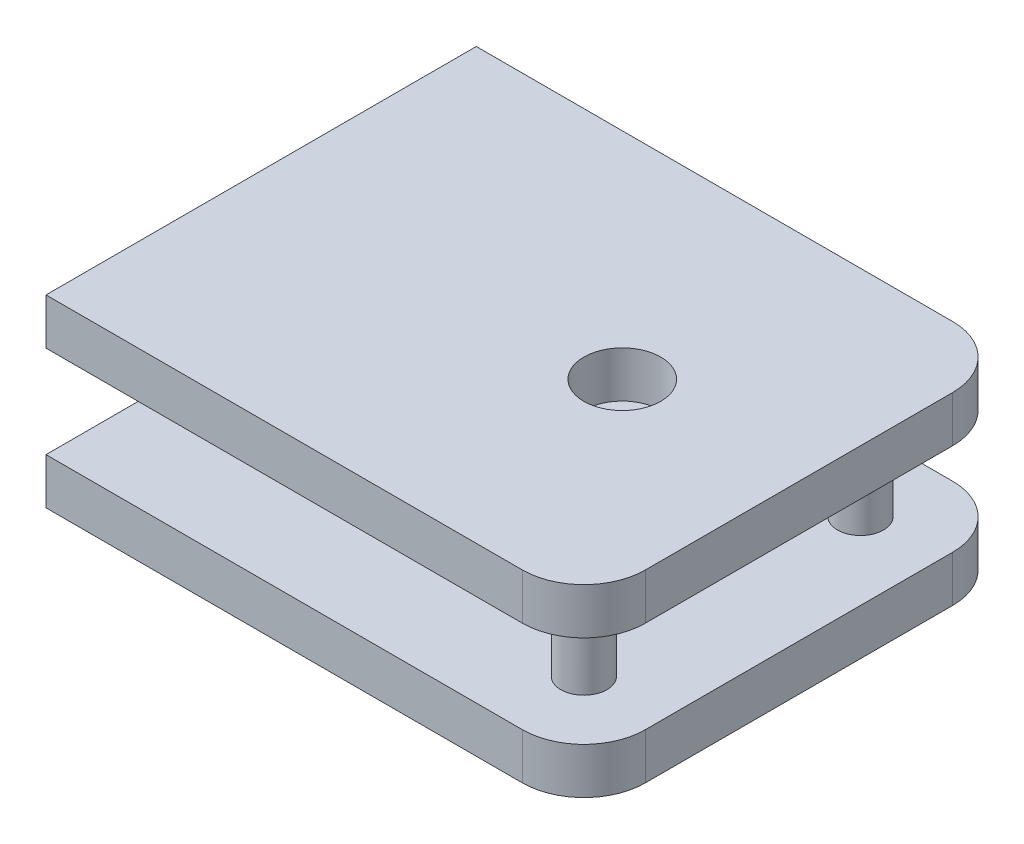
SolidWorks part; units mm, degrees
ref_plane "Alzado" through (0, 0, 0) normal (0, 0, 1) x (1, 0, 0)
ref_plane "Planta" through (0, 0, 0) normal (0, 1, 0) x (1, 0, 0)
ref_plane "Vista lateral" through (0, 0, 0) normal (1, 0, 0) x (0, 0, -1)
sketch "Croquis1" plane through (0, 175.406, 0) normal (0, -1, 0) x (-1, 0, 0)
  line L1 (159.0629, 2.3644) -> (190.0629, 2.3644)
  line L2 (155.0629, -1.6356) -> (155.0629, -21.6356)
  line L3 (159.0629, -25.6356) -> (190.0629, -25.6356)
  line L4 (190.0629, 2.3644) -> (190.0629, -25.6356)
  arc A2 (155.0629, -21.6356) -> (159.0629, -25.6356) centre (159.0629, -21.6356) ccw
  arc A3 (159.0629, 2.3644) -> (155.0629, -1.6356) centre (159.0629, -1.6356) ccw
  point P6 (155.0629, -25.6356)
  point P9 (155.0629, 2.3644)
  dimension "D3" = 4
  dimension "D1" = 28
  dimension "D2" = 35
extrude "Saliente-Extruir1" add sketch "Croquis1" along normal blind 3
sketch "Croquis2" plane through (0, 175.406, 0) normal (0, 1, 0) x (1, 0, 0)
  line L0 (-160.0629, -2.6356) -> (-160.0629, -20.6356) construction
  line L1 (-190.0629, -11.6356) -> (-160.0629, -11.6356) construction
  line L2 (-190.0629, -25.6356) -> (-190.0629, 2.3644) construction
  line L3 (-155.0629, -1.6356) -> (-155.0629, -21.6356) construction
  circle A0 centre (-160.0629, -2.6356) radius 1.5
  circle A1 centre (-160.0629, -20.6356) radius 1.5
  point P10 (-160.0629, -21.3135)
  dimension "D2" = 3
  dimension "D1" = 5
  dimension "D3" = 18
extrude "Saliente-Extruir2" add sketch "Croquis2" along normal blind 6
sketch "Croquis3" plane through (0, 181.406, 0) normal (0, 1, 0) x (1, 0, 0)
  line L4 (-190.0629, 2.3644) -> (-190.0629, -25.6356)
  line L5 (-190.0629, -25.6356) -> (-159.0629, -25.6356)
  line L6 (-155.0629, -21.6356) -> (-155.0629, -1.6356)
  line L7 (-159.0629, 2.3644) -> (-190.0629, 2.3644)
  line L8 (-190.0629, 2.3644) -> (-190.0629, -25.6356)
  line L9 (-190.0629, -25.6356) -> (-159.0629, -25.6356)
  line L10 (-155.0629, -21.6356) -> (-155.0629, -1.6356)
  line L11 (-159.0629, 2.3644) -> (-190.0629, 2.3644)
  arc A2 (-159.0629, -25.6356) -> (-155.0629, -21.6356) centre (-159.0629, -21.6356) ccw
  arc A3 (-155.0629, -1.6356) -> (-159.0629, 2.3644) centre (-159.0629, -1.6356) ccw
  arc A4 (-159.0629, -25.6356) -> (-155.0629, -21.6356) centre (-159.0629, -21.6356) ccw
  arc A5 (-155.0629, -1.6356) -> (-159.0629, 2.3644) centre (-159.0629, -1.6356) ccw
  dimension "D1" = 0
extrude "Saliente-Extruir3" add sketch "Croquis3" along normal blind 3
sketch "Croquis4" plane through (0, 184.406, 0) normal (0, 1, 0) x (1, 0, 0)
  line L0 (-166.5629, -11.6356) -> (-155.0629, -11.6356) construction
  line L1 (-155.0629, -21.6356) -> (-155.0629, -1.6356) construction
  circle A0 centre (-166.5629, -11.6356) radius 2.5
  point P2 (-171.2001, -11.6356)
  dimension "D1" = 5
  dimension "D2" = 11.5
extrude "Cortar-Extruir1" cut sketch "Croquis4" against normal up to surface (12 mm away) up to face at (-167.7868, 172.406, 11.6356)
